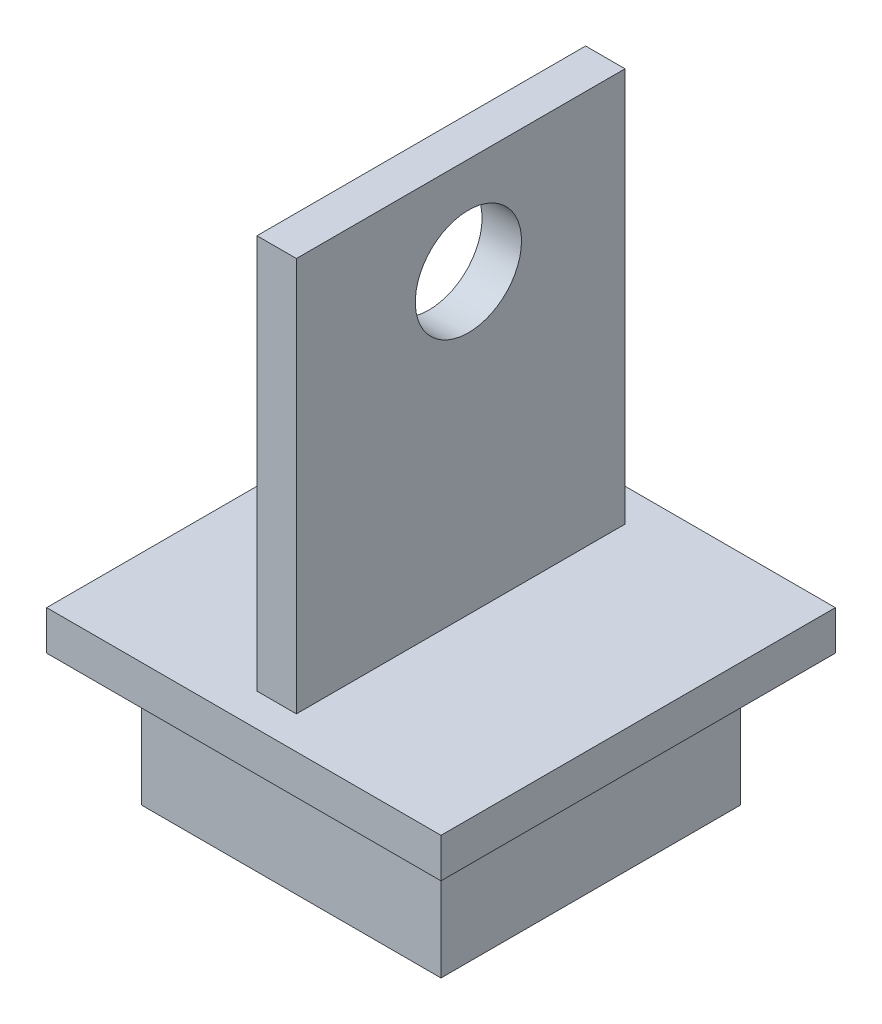
SolidWorks part; units mm, degrees
ref_plane "Alzado" through (0, 0, 0) normal (0, 0, 1) x (1, 0, 0)
ref_plane "Planta" through (0, 0, 0) normal (0, 1, 0) x (1, 0, 0)
ref_plane "Vista lateral" through (0, 0, 0) normal (1, 0, 0) x (0, 0, -1)
sketch "Croquis1" plane through (0, 0, 0) normal (0, 1, 0) x (1, 0, 0)
  line L1 (-15, 15) -> (15, 15)
  line L2 (-15, 15) -> (-15, -15)
  line L3 (-15, -15) -> (15, -15)
  line L4 (15, 15) -> (15, -15)
  line L5 (-15, 15) -> (15, -15) construction
  line L6 (-15, -15) -> (15, 15) construction
  point P0 (0, 0)
  dimension "D1" = 30
  dimension "D2" = 30
extrude "Saliente-Extruir1" add sketch "Croquis1" along normal blind 3
sketch "Croquis2" plane through (0, 3, 0) normal (0, 1, 0) x (1, 0, 0)
  line L1 (-1.5, 12.5) -> (1.5, 12.5)
  line L2 (-1.5, 12.5) -> (-1.5, -12.5)
  line L3 (-1.5, -12.5) -> (1.5, -12.5)
  line L4 (1.5, 12.5) -> (1.5, -12.5)
  line L5 (0, -15) -> (0, 15) construction
  line L6 (-15, -15) -> (15, -15) construction
  line L7 (15, 15) -> (-15, 15) construction
  line L8 (-15, 0) -> (15, 0) construction
  line L9 (-15, 15) -> (-15, -15) construction
  line L10 (15, -15) -> (15, 15) construction
  dimension "D1" = 25
  dimension "D2" = 3
extrude "Saliente-Extruir2" add sketch "Croquis2" along normal blind 30
sketch "Croquis3" plane through (1.5, 0, 0) normal (1, 0, 0) x (0, 0, -1)
  circle A0 centre (0.5847, 25.6037) radius 4.0394
extrude "Cortar-Extruir1" cut sketch "Croquis3" against normal blind 10
sketch "Croquis4" plane through (0, 0, 0) normal (0, -1, 0) x (1, 0, 0)
  line L0 (15, 15) -> (15, -15) construction
  line L1 (-11.4, 11.4) -> (11.4, 11.4)
  line L2 (-11.4, 11.4) -> (-11.4, -11.4)
  line L3 (-11.4, -11.4) -> (11.4, -11.4)
  line L4 (11.4, 11.4) -> (11.4, -11.4)
  line L5 (-11.4, 11.4) -> (11.4, -11.4) construction
  line L6 (-11.4, -11.4) -> (11.4, 11.4) construction
  line L7 (-8.4, 8.4) -> (8.4, 8.4)
  line L8 (-8.4, 8.4) -> (-8.4, -8.4)
  line L9 (-8.4, -8.4) -> (8.4, -8.4)
  line L10 (8.4, 8.4) -> (8.4, -8.4)
  line L11 (-8.4, 8.4) -> (8.4, -8.4) construction
  line L12 (-8.4, -8.4) -> (8.4, 8.4) construction
  line L13 (15, -15) -> (-15, -15) construction
  point P0 (0, 0)
  point P6 (0, 0)
  dimension "D1" = 3
  dimension "D2" = 3.6
  dimension "D3" = 3.6
extrude "Saliente-Extruir3" add sketch "Croquis4" along normal blind 10
